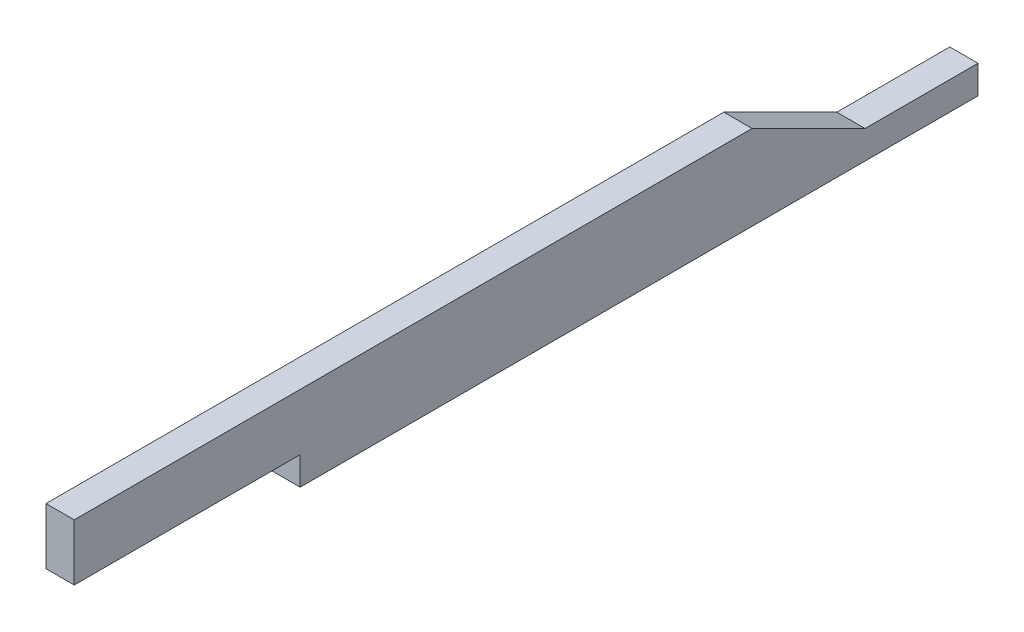
SolidWorks part; units mm, degrees
ref_plane "Front Plane" through (0, 0, 0) normal (0, 0, 1) x (1, 0, 0)
ref_plane "Top Plane" through (0, 0, 0) normal (0, 1, 0) x (1, 0, 0)
ref_plane "Right Plane" through (0, 0, 0) normal (1, 0, 0) x (0, 0, -1)
sketch "Sketch1" plane through (0, 0, 0) normal (0, 0, 1) x (1, 0, 0)
  line L1 (0, 0) -> (-6.35, 0)
  line L2 (0, 0) -> (0, 19.05)
  line L3 (0, 19.05) -> (-6.35, 19.05)
  line L4 (-6.35, 0) -> (-6.35, 19.05)
  dimension "D1" = 6.35
  dimension "D2" = 19.05
extrude "Boss-Extrude1" add sketch "Sketch1" along normal blind 203.2
sketch "Sketch2" plane through (-6.35, 0, 0) normal (-1, 0, 0) x (0, 0, 1)
  line L1 (203.2, 0) -> (152.4, 0)
  line L2 (203.2, 0) -> (203.2, 6.35)
  line L3 (203.2, 6.35) -> (152.4, 6.35)
  line L4 (152.4, 0) -> (152.4, 6.35)
  dimension "D1" = 6.35
  dimension "D2" = 50.8
extrude "Cut-Extrude1" cut sketch "Sketch2" against normal blind 203.2
sketch "Sketch3" plane through (-6.35, 0, 0) normal (-1, 0, 0) x (0, 0, 1)
  line L0 (0, 6.35) -> (25.4, 6.35)
  line L1 (0, 19.05) -> (0, 0) construction
  line L2 (25.4, 6.35) -> (50.8, 19.05)
  line L3 (203.2, 19.05) -> (0, 19.05) construction
  line L4 (50.8, 19.05) -> (0, 19.05)
  line L5 (0, 19.05) -> (0, 6.35)
  dimension "D1" = 12.7
  dimension "D2" = 50.8
  dimension "D3" = 25.4
extrude "Cut-Extrude2" cut sketch "Sketch3" against normal blind 203.2
